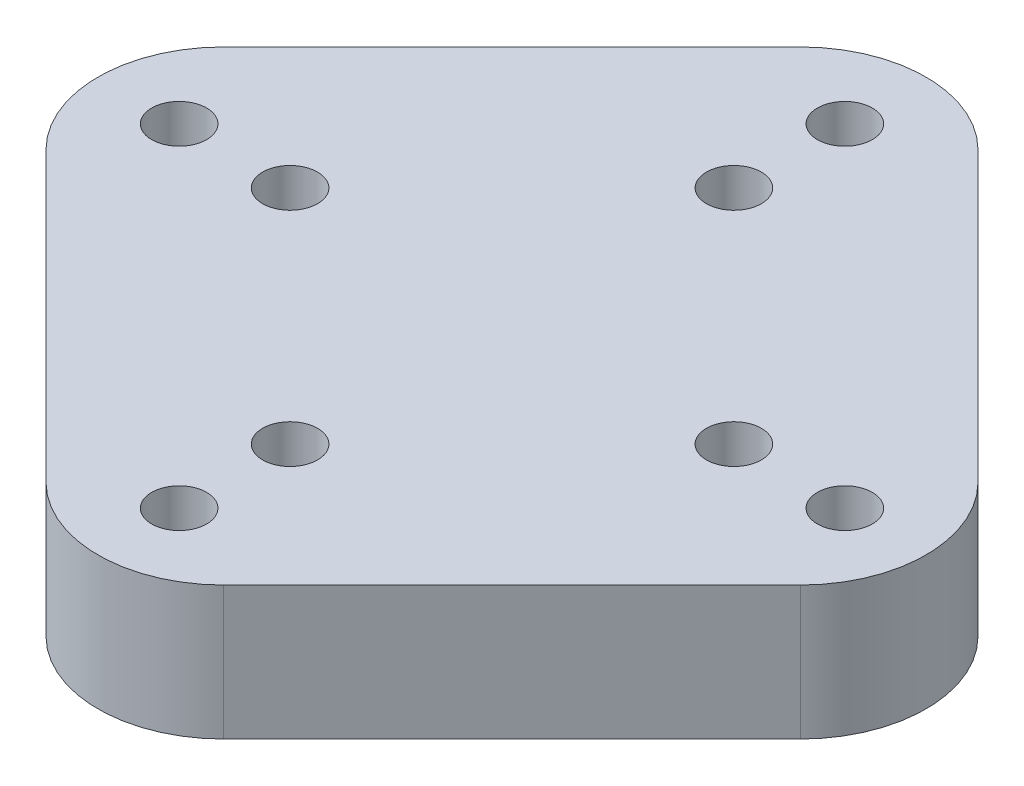
SolidWorks part; units mm, degrees
ref_plane "Спереди" through (0, 0, 0) normal (0, 0, 1) x (1, 0, 0)
ref_plane "Сверху" through (0, 0, 0) normal (0, 1, 0) x (1, 0, 0)
ref_plane "Справа" through (0, 0, 0) normal (1, 0, 0) x (0, 0, -1)
sketch "Эскиз1" plane through (0, 0, 0) normal (0, 1, 0) x (1, 0, 0)
  line L4 (0, 0) -> (29.6985, 0) construction
  line L5 (5.6569, -24.0416) -> (24.0416, -5.6569)
  line L6 (24.0416, 5.6569) -> (5.6569, 24.0416)
  line L7 (-5.6569, 24.0416) -> (-24.0416, 5.6569)
  line L8 (-24.0416, -5.6569) -> (-5.6569, -24.0416)
  line L10 (21.2132, 0) -> (0, 21.2132) construction
  line L11 (0, 21.2132) -> (-21.2132, 0) construction
  line L12 (-21.2132, 0) -> (0, -21.2132) construction
  line L13 (0, -21.2132) -> (21.2132, 0) construction
  line L14 (0, 14.1421) -> (-14.1421, 0) construction
  line L15 (-14.1421, 0) -> (0, -14.1421) construction
  line L16 (0, -14.1421) -> (14.1421, 0) construction
  line L17 (14.1421, 0) -> (0, 14.1421) construction
  circle A0 centre (0, 0) radius 21 construction
  circle A1 centre (21.2132, 0) radius 1.75
  circle A2 centre (14.1421, 0) radius 1.75
  circle A3 centre (0, -14.1421) radius 1.75
  circle A4 centre (0, -21.2132) radius 1.75
  circle A5 centre (-14.1421, 0) radius 1.75
  circle A6 centre (-21.2132, 0) radius 1.75
  circle A7 centre (0, 14.1421) radius 1.75
  circle A8 centre (0, 21.2132) radius 1.75
  circle A11 centre (0, 0) radius 15 construction
  circle A12 centre (0, 0) radius 10 construction
  arc A13 (24.0416, 5.6569) -> (24.0416, -5.6569) centre (18.3848, 0) cw
  arc A14 (5.6569, -24.0416) -> (-5.6569, -24.0416) centre (0, -18.3848) cw
  arc A15 (-24.0416, -5.6569) -> (-24.0416, 5.6569) centre (-18.3848, 0) cw
  arc A16 (-5.6569, 24.0416) -> (5.6569, 24.0416) centre (0, 18.3848) cw
  point P36 (-29.6985, 0)
  point P39 (0, 29.6985)
  dimension "D2" = 3.5
  dimension "D3" = 3.5
  dimension "D5" = 30
  dimension "D7" = 8
  dimension "D1" = 42
  dimension "D6" = 20
  dimension "D4" = 4
extrude "Бобышка-Вытянуть1" add sketch "Эскиз1" along normal blind 8.5
equation "\"print_offset\"= 0.5"
equation "\"tape_width\"=51"
equation "\"tape_thikness\"=5"
equation "\"tape_distance\"=5"
equation "\"screw_d\"=3"
equation "\"screw_hh_d\"=5.3"
equation "\"nut_d\"=5.5"
equation "\"nut_h\"=2.5"
equation "\"sitting_screws\"=30"
equation "\"mount_size\"=42"
equation "\"D1@Эскиз1\"=\"mount_size\""
equation "\"D2@Эскиз1\"=\"screw_d\"+\"print_offset\""
equation "\"D3@Эскиз1\"=\"D2@Эскиз1\""
equation "\"D5@Эскиз1\"=\"sitting_screws\""
equation "\"D6@Эскиз1\"=\"D5@Эскиз1\"*2/3"
